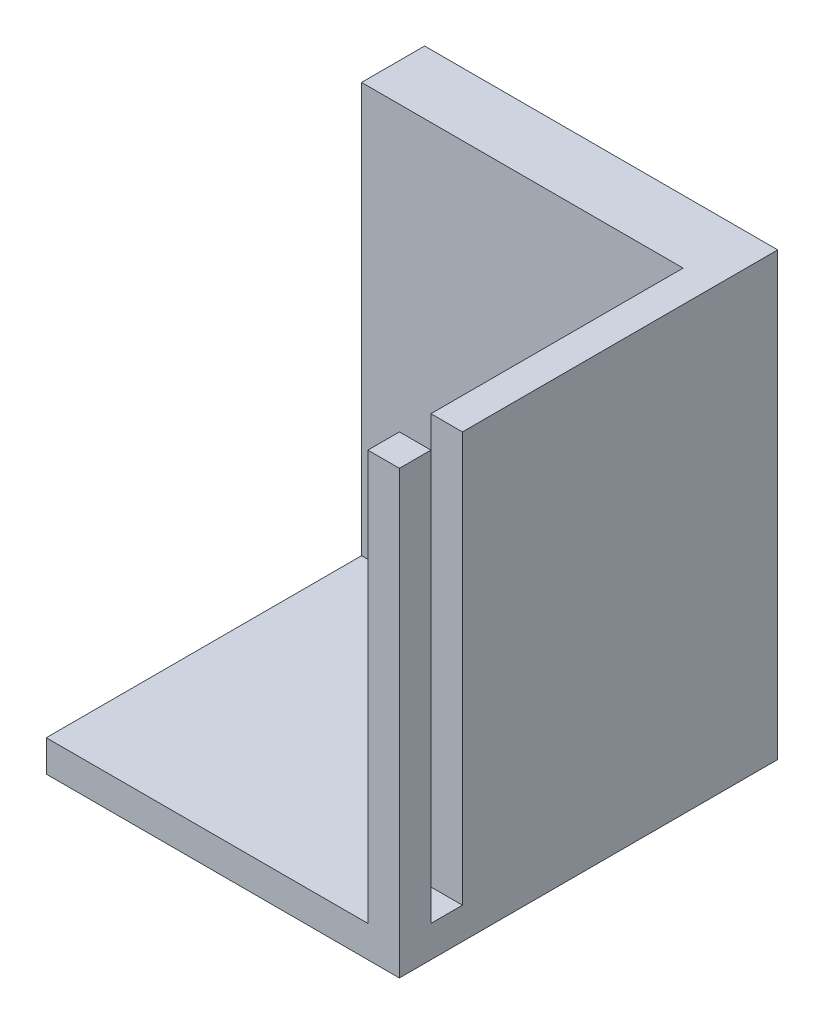
SolidWorks part; units mm, degrees
ref_plane "정면" through (0, 0, 0) normal (0, 0, 1) x (1, 0, 0)
ref_plane "윗면" through (0, 0, 0) normal (0, 1, 0) x (1, 0, 0)
ref_plane "우측면" through (0, 0, 0) normal (1, 0, 0) x (0, 0, -1)
sketch "Sketch1" plane through (0, 0, 0) normal (0, 1, 0) x (1, 0, 0)
  line L1 (0, 0) -> (670, 0)
  line L2 (0, 0) -> (0, 120)
  line L3 (0, 120) -> (670, 120)
  line L4 (670, 0) -> (670, 120)
  dimension "700" = 670
  dimension "D2" = 120
extrude "Boss-Extrude1" add sketch "Sketch1" along normal blind 530
sketch "Sketch2" plane through (0, 0, 0) normal (0, 0, 1) x (1, 0, 0)
  line L0 (0, 530) -> (0, 0) construction
  line L1 (10, 280) -> (110, 280)
  line L2 (10, 280) -> (10, 480)
  line L3 (10, 480) -> (110, 480)
  line L4 (110, 280) -> (110, 480)
  line L5 (0, 0) -> (670, 0) construction
  line L6 (120, 280) -> (120, 480)
  line L7 (120, 280) -> (220, 280)
  line L8 (220, 280) -> (220, 480)
  line L9 (120, 480) -> (220, 480)
  line L10 (230, 280) -> (230, 480)
  line L11 (230, 280) -> (330, 280)
  line L12 (330, 280) -> (330, 480)
  line L13 (230, 480) -> (330, 480)
  line L14 (340, 280) -> (340, 480)
  line L15 (340, 280) -> (440, 280)
  line L16 (440, 280) -> (440, 480)
  line L17 (340, 480) -> (440, 480)
  line L18 (450, 280) -> (450, 480)
  line L19 (450, 280) -> (550, 280)
  line L20 (550, 280) -> (550, 480)
  line L21 (450, 480) -> (550, 480)
  line L22 (560, 280) -> (560, 480)
  line L23 (560, 280) -> (660, 280)
  line L24 (660, 280) -> (660, 480)
  line L25 (560, 480) -> (660, 480)
  line L27 (10, 10) -> (660, 10)
  line L28 (10, 10) -> (10, 260)
  line L29 (10, 260) -> (660, 260)
  line L30 (660, 10) -> (660, 260)
  line L31 (0, 530) -> (670, 530) construction
  point P6 (10, 380)
  dimension "D1" = 100
  dimension "D2" = 200
  dimension "D3" = 10
  dimension "D4" = 50
  dimension "D6" = 10
  dimension "D7" = 20
  dimension "D5" = 6
extrude "Cut-Extrude1" cut sketch "Sketch2" against normal blind 100
sketch "Sketch3" plane through (0, 530, 0) normal (0, 1, 0) x (1, 0, 0)
  line L1 (670, 120) -> (0, 120) construction
  line L2 (0, 120) -> (0, 0) construction
  circle A0 centre (60, 60) radius 50
  circle A1 centre (170, 60) radius 50
  circle A2 centre (280, 60) radius 50
  circle A3 centre (390, 60) radius 50
  circle A4 centre (500, 60) radius 50
  circle A5 centre (610, 60) radius 50
  dimension "D1" = 100
  dimension "D2" = 10
  dimension "D3" = 10
  dimension "D4" = 6
extrude "Cut-Extrude2" cut sketch "Sketch3" against normal blind 260
hole_wizard "Ø12.0 (12) Diameter Hole2" positions "3DSketch1" profile "Sketch7" hole size "Ø12.0" standard "Ansi Metric"
sketch3d "3DSketch1"
  point P0 (59.7046, 270, -102.4117)
  point P2 (171.5567, 270, -102.6076)
  point P4 (280.8723, 270, -102.3969)
  point P6 (391.0687, 270, -102.7535)
  point P8 (500.7133, 270, -101.754)
  point P10 (609.5165, 270, -101.1227)
sketch "Sketch7" plane through (59.7046, 270, -102.4117) normal (1, 0, 0) x (0, 0, 1)
  line L0 (0, 0) -> (0, 33.6052)
  line L1 (0, 33.6052) -> (6, 30)
  line L2 (6, 30) -> (6, 0)
  line L5 (6, 0) -> (0, 0)
  line L10 (0, 33.6052) -> (-6, 30) construction
  line L11 (0, -6.35) -> (0, 107.95) construction
  dimension "구멍 지름" = 12
  dimension "구멍 깊이" = 30
  dimension "드릴 각도" = 118
sketch "Sketch8" plane through (0, 0, 0) normal (0, 0, 1) x (1, 0, 0)
  line L0 (660, 280) -> (660, 480) construction
  line L1 (10, 280) -> (660, 280)
  line L2 (10, 280) -> (10, 330)
  line L3 (10, 330) -> (660, 330)
  line L4 (660, 280) -> (660, 330)
  dimension "D1" = 50
extrude "Boss-Extrude2" add sketch "Sketch8" against normal blind 5
sketch "Sketch9" plane through (670, 0, 0) normal (1, 0, 0) x (0, 0, -1)
  line L0 (0, 530) -> (0, 0) construction
  line L1 (10, 10) -> (20, 10)
  line L2 (10, 10) -> (10, 260)
  line L3 (10, 260) -> (20, 260)
  line L4 (20, 10) -> (20, 260)
  line L5 (0, 0) -> (120, 0) construction
  dimension "D1" = 10
  dimension "D2" = 10
  dimension "D3" = 10
  dimension "D4" = 250
extrude "Cut-Extrude3" cut sketch "Sketch9" against normal blind 717
sketch "Sketch10" plane through (0, 10, 0) normal (0, 1, 0) x (1, 0, 0)
  line L0 (670, 120) -> (0, 120) construction
  line L1 (365, 61.9436) -> (350, 87.9243)
  line L2 (350, 87.9243) -> (320, 87.9243)
  line L3 (320, 87.9243) -> (305, 61.9436)
  line L4 (305, 61.9436) -> (320, 35.9628)
  line L5 (320, 35.9628) -> (350, 35.9628)
  line L6 (350, 35.9628) -> (365, 61.9436)
  line L7 (0, 120) -> (0, 0) construction
  circle A0 centre (335, 61.9436) radius 25.9808 construction
  dimension "D1" = 60
  dimension "D2" = 305
extrude "Cut-Extrude4" cut sketch "Sketch10" against normal blind 5
sketch "Sketch11" plane through (0, 0, -100) normal (0, 0, 1) x (1, 0, 0)
  line L0 (10, 10) -> (660, 10) construction
  line L1 (250, 10) -> (260, 10)
  line L2 (250, 10) -> (250, 110)
  line L3 (250, 110) -> (260, 110)
  line L4 (260, 10) -> (260, 110)
  line L5 (660, 10) -> (660, 260) construction
  line L6 (410, 10) -> (420, 10)
  line L7 (410, 10) -> (410, 110)
  line L8 (410, 110) -> (420, 110)
  line L9 (420, 10) -> (420, 110)
  line L10 (25, 198.4569) -> (325, 145.5588)
  line L11 (325, 145.5588) -> (325, 122.0178)
  line L12 (325, 122.0178) -> (345, 122.0178)
  line L13 (345, 122.0178) -> (345, 145.5588)
  line L14 (345, 145.5588) -> (645, 198.4569)
  line L15 (645, 198.4569) -> (25, 198.4569)
  point P18 (345, 133.7883)
  dimension "D1" = 10
  dimension "D2" = 10
  dimension "D3" = 100
  dimension "D4" = 100
  dimension "D5" = 150
  dimension "D6" = 240
  dimension "D7" = 20
  dimension "D8" = 65
  dimension "D9" = 100
  dimension "D10" = 620
  dimension "D11" = 100
extrude "Boss-Extrude3" add sketch "Sketch11" along normal blind 78 separate body
sketch "Sketch12" plane through (0, 0, -100) normal (0, 0, 1) x (1, 0, 0)
  line L0 (660, 260) -> (10, 260) construction
  line L1 (75.1986, 260) -> (95.1986, 260)
  line L2 (75.1986, 260) -> (75.1986, 230)
  line L3 (75.1986, 230) -> (95.1986, 230)
  line L4 (95.1986, 260) -> (95.1986, 230)
  line L5 (65.1986, 260) -> (65.1986, 240) construction
  line L6 (185.1986, 260) -> (185.1986, 230)
  line L7 (185.1986, 260) -> (205.1986, 260)
  line L8 (205.1986, 260) -> (205.1986, 230)
  line L9 (185.1986, 230) -> (205.1986, 230)
  line L10 (295.1986, 260) -> (295.1986, 230)
  line L11 (295.1986, 260) -> (315.1986, 260)
  line L12 (315.1986, 260) -> (315.1986, 230)
  line L13 (295.1986, 230) -> (315.1986, 230)
  line L14 (405.1986, 260) -> (405.1986, 230)
  line L15 (405.1986, 260) -> (425.1986, 260)
  line L16 (425.1986, 260) -> (425.1986, 230)
  line L17 (405.1986, 230) -> (425.1986, 230)
  line L18 (515.1986, 260) -> (515.1986, 230)
  line L19 (515.1986, 260) -> (535.1986, 260)
  line L20 (535.1986, 260) -> (535.1986, 230)
  line L21 (515.1986, 230) -> (535.1986, 230)
  line L22 (625.1986, 260) -> (625.1986, 230)
  line L23 (625.1986, 260) -> (645.1986, 260)
  line L24 (645.1986, 260) -> (645.1986, 230)
  line L25 (625.1986, 230) -> (645.1986, 230)
  dimension "D1" = 20
  dimension "D2" = 30
  dimension "D3" = 10
  dimension "D4" = 6
extrude "Cut-Extrude5" cut sketch "Sketch12" against normal blind 80
sketch "Sketch15" plane through (345, 0, 0) normal (1, 0, 0) x (0, 0, -1)
  line L0 (20, 10) -> (20, 260) construction
  line L1 (20, 121.4638) -> (50, 121.4638)
  line L2 (20, 121.4638) -> (20, 145)
  line L3 (20, 145) -> (50, 145)
  line L4 (50, 121.4638) -> (50, 145)
  line L5 (120, 530) -> (120, 0) construction
  line L6 (100, 116.0134) -> (70, 116.0134)
  line L7 (100, 116.0134) -> (100, 145)
  line L8 (100, 145) -> (70, 145)
  line L9 (70, 116.0134) -> (70, 145)
  line L10 (20, 260) -> (10, 260) construction
  dimension "D1" = 20
  dimension "D2" = 20
  dimension "D3" = 115
  dimension "D4" = 30
extrude "Cut-Extrude7" cut sketch "Sketch15" against normal blind 35
shell "Shell1" thickness 3
sketch "Sketch16" plane through (0, 122.0178, 0) normal (0, -1, 0) x (1, 0, 0)
  line L0 (345, -50) -> (325, -50) construction
  line L1 (328, -53) -> (342, -53)
  line L2 (328, -53) -> (328, -67)
  line L3 (328, -67) -> (342, -67)
  line L4 (342, -53) -> (342, -67)
  line L5 (325, -50) -> (325, -70) construction
  line L6 (345, -50) -> (345, -70) construction
  line L7 (325, -70) -> (345, -70) construction
  dimension "D1" = 3
  dimension "D2" = 3
  dimension "D3" = 3
  dimension "D4" = 3
extrude "Cut-Extrude8" cut sketch "Sketch16" against normal blind 35
sketch "Sketch17" plane through (0, 0, 0) normal (0, 0, 1) x (1, 0, 0)
  text T0 "<b>DIFF_USER</b>" font "Britannic Bold" height in points 72
extrude "Boss-Extrude4" add sketch "Sketch17" along normal blind 5
sketch "Sketch18" plane through (0, 0, 0) normal (0, 0, 1) x (1, 0, 0)
  line L0 (0, 530) -> (670, 530) construction
  line L1 (0, 530) -> (670, 530)
  line L2 (0, 530) -> (0, 280)
  line L3 (0, 280) -> (670, 280)
  line L4 (670, 530) -> (670, 280)
  line L5 (670, 530) -> (670, 0) construction
  line L6 (0, 0) -> (670, 0) construction
  dimension "D1" = 280
extrude "Cut-Extrude10" cut sketch "Sketch18" against normal through all both and the other way through all
delete or keep bodies "Body-Delete/Keep 1" type delete bodies bodies 109 115 112
sketch "Sketch19" plane through (0, 0, -120) normal (0, 0, -1) x (-1, 0, 0)
  line L0 (0, 280) -> (-670, 280) construction
  line L1 (0, 0) -> (-558, 0)
  line L2 (0, 0) -> (0, 280)
  line L3 (0, 280) -> (-558, 280)
  line L4 (-558, 0) -> (-558, 280)
  line L5 (-670, 280) -> (-670, 0) construction
  dimension "D1" = 112
extrude "Cut-Extrude12" cut sketch "Sketch19" against normal through all both and the other way through all
sketch "Sketch20" plane through (660, 0, 0) normal (-1, 0, 0) x (0, 0, 1)
  line L0 (0, 10) -> (0, 260) construction
  line L1 (-120, 280) -> (0, 280)
  line L2 (-120, 280) -> (-120, 140)
  line L3 (-120, 140) -> (0, 140)
  line L4 (0, 280) -> (0, 140)
  dimension "D1" = 140
extrude "Cut-Extrude13" cut sketch "Sketch20" against normal through all both and the other way through all
